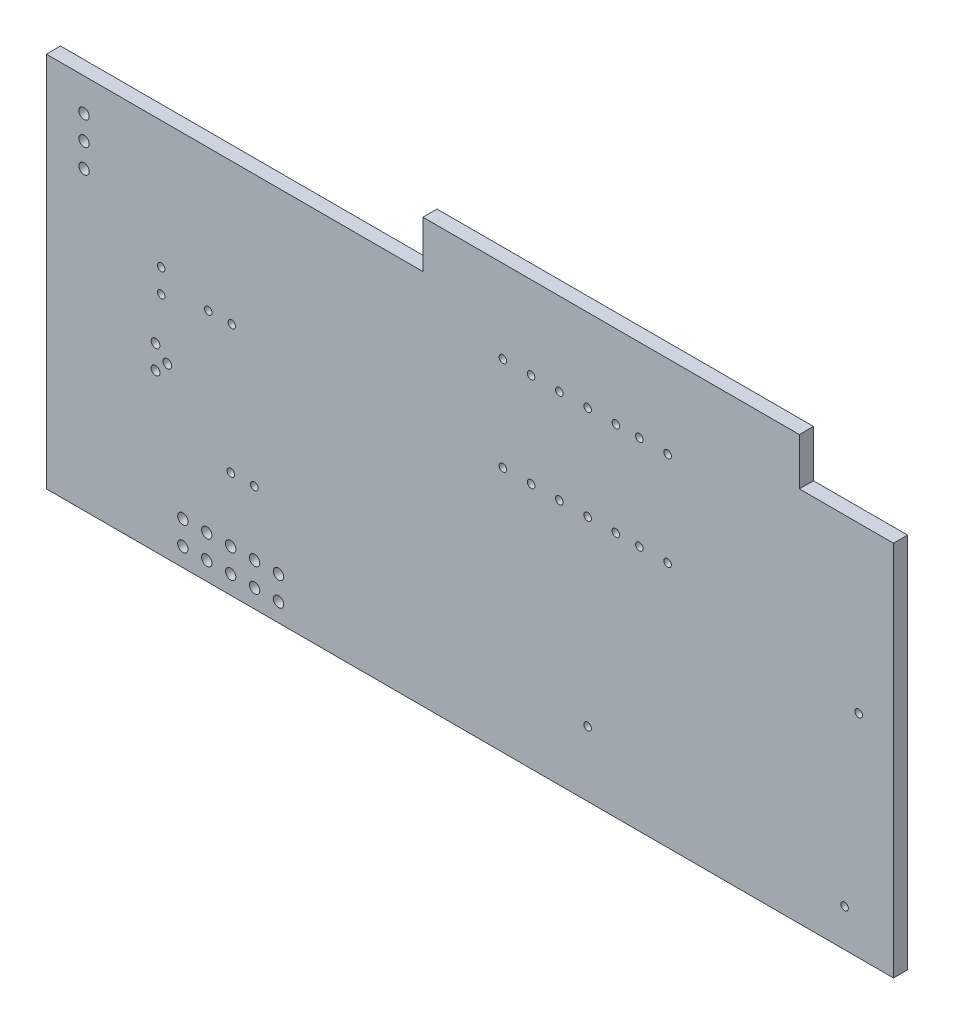
SolidWorks part; units mm, degrees
ref_plane "Спереди" through (0, 0, 0) normal (0, 0, 1) x (1, 0, 0)
ref_plane "Сверху" through (0, 0, 0) normal (0, 1, 0) x (1, 0, 0)
ref_plane "Справа" through (0, 0, 0) normal (1, 0, 0) x (0, 0, -1)
sketch "Эскиз1" plane through (0, 0, 0) normal (0, 0, 1) x (1, 0, 0)
  line L0 (0, 20) -> (0, 25)
  line L1 (-40, -20) -> (50, -20)
  line L2 (-40, -20) -> (-40, 20)
  line L3 (-40, 20) -> (0, 20)
  line L4 (50, -20) -> (50, 20)
  line L5 (0, 25) -> (40, 25)
  line L6 (40, 25) -> (40, 20)
  line L7 (40, 20) -> (50, 20)
  dimension "D1" = 90
  dimension "D2" = 40
  dimension "D3" = 40
  dimension "D4" = 40
  dimension "D5" = 5
  dimension "D6" = 20
extrude "Вытянуть1" add sketch "Эскиз1" along normal blind 1.5
sketch "Эскиз2" plane through (0, 0, 1.5) normal (0, 0, 1) x (1, 0, 0)
  line L0 (-40, 20) -> (-40, -20) construction
  line L1 (-40, -20) -> (50, -20) construction
  circle A0 centre (-36, 16.54) radius 0.55
  circle A1 centre (-36, 11.46) radius 0.55
  circle A2 centre (-36, 14) radius 0.55
  circle A3 centre (-25.5, -15.5) radius 0.55
  circle A4 centre (-25.5, -18.04) radius 0.55
  circle A5 centre (-22.96, -15.5) radius 0.55
  circle A6 centre (-22.96, -18.04) radius 0.55
  circle A7 centre (-20.42, -15.5) radius 0.55
  circle A8 centre (-20.42, -18.04) radius 0.55
  circle A9 centre (-17.88, -15.5) radius 0.55
  circle A10 centre (-17.88, -18.04) radius 0.55
  circle A11 centre (-15.34, -15.5) radius 0.55
  circle A12 centre (-15.34, -18.04) radius 0.55
  dimension "D1" = 5.08
  dimension "D3" = 36.54
  dimension "D4" = 1.1
  dimension "D5" = 2.54
  dimension "D8" = 1.1
  dimension "D9" = 2.54
  dimension "D2" = 4
  dimension "D6" = 4.5
  dimension "D7" = 14.5
  dimension "D10" = 14.5
extrude "Вырез-Вытянуть1" cut sketch "Эскиз2" against normal blind 1.5
sketch "Эскиз3" plane through (0, 0, 1.5) normal (0, 0, 1) x (1, 0, 0)
  line L0 (-40, -20) -> (50, -20) construction
  line L1 (-40, 20) -> (-40, -20) construction
  line L2 (8.5, 16.2) -> (8.5, 4.0182) construction
  line L3 (-40, -20) -> (50, -20) construction
  line L4 (8.5, 16.2) -> (28.1359, 16.2) construction
  line L5 (-40, 20) -> (-40, -20) construction
  line L6 (11.5, 16.2) -> (11.5, 4.0182) construction
  line L7 (14.5, 16.2) -> (14.5, 4.0182) construction
  line L8 (17.5, 16.2) -> (17.5, 4.0182) construction
  line L9 (20.5, 16.2) -> (20.5, 4.0182) construction
  line L10 (23.5, 16.2) -> (23.5, 4.0182) construction
  line L11 (26.5, 16.2) -> (26.5, 4.0182) construction
  line L12 (-20.4027, -8.7) -> (-16.725, -8.7) construction
  line L14 (-22.8, 5) -> (-16.1369, 5) construction
  line L15 (50, -20) -> (50, 20) construction
  line L20 (28.9777, 16.2) -> (21.3084, 16.2) construction
  line L30 (-31.875, 0.5) -> (-34.4855, 0.5) construction
  line L34 (-20.4027, -8.7) -> (-20.4027, -7.5412) construction
  line L35 (-20.4027, -7.5412) -> (-13.1239, -7.5412) construction
  line L36 (-22.8, 5) -> (-22.8, -7.5) construction
  line L37 (-27.8, 4) -> (-27.8, 6.5) construction
  circle A0 centre (-17.9027, -8.7) radius 0.4
  circle A1 centre (-20.3, 5) radius 0.4
  circle A12 centre (8.5, 16.2) radius 0.4
  circle A13 centre (8.5, 6.2) radius 0.4
  circle A16 centre (11.5, 16.2) radius 0.4
  circle A17 centre (11.5, 6.2) radius 0.4
  circle A18 centre (14.5, 16.2) radius 0.4
  circle A19 centre (14.5, 6.2) radius 0.4
  circle A20 centre (17.5, 16.2) radius 0.4
  circle A21 centre (17.5, 6.2) radius 0.4
  circle A22 centre (20.5, 16.2) radius 0.4
  circle A23 centre (20.5, 6.2) radius 0.4
  circle A42 centre (23, 16.2) radius 0.4
  circle A51 centre (23, 6.2) radius 0.4
  circle A52 centre (26, 16.2) radius 0.4
  circle A53 centre (26, 6.2) radius 0.4
  circle A71 centre (-20.4027, -8.7) radius 0.4
  circle A73 centre (-22.8, 5) radius 0.4
  circle A74 centre (-27.8, 6.5) radius 0.4
  circle A75 centre (-27.8, 4) radius 0.4
  dimension "D2" = 3
  dimension "D3" = 0.8
  dimension "D15" = 36.2
  dimension "D16" = 24
  dimension "D40" = 10
  dimension "D41" = 10
  dimension "D65" = 2.5
  dimension "D5" = 2.5
  dimension "D7" = 24
  dimension "D8" = 12.2
  dimension "D9" = 2.5
  dimension "D10" = 3
  dimension "D11" = 3
  dimension "D12" = 3
  dimension "D13" = 3
  dimension "D14" = 3
  dimension "D47" = 20.5
  dimension "D66" = 17.2
extrude "Вырез-Вытянуть2" cut sketch "Эскиз3" against normal blind 10
sketch "Эскиз6" plane through (0, 0, 1.5) normal (0, 0, 1) x (1, 0, 0)
  line L0 (-28.4, 1.4874) -> (-28.4, -3.7541) construction
  line L1 (-25.3934, -2.05) -> (-18.4226, -2.05) construction
  line L2 (-40, 20) -> (-40, -20) construction
  line L3 (-40, -20) -> (50, -20) construction
  line L4 (-40, -20) -> (50, -20) construction
  line L5 (50, -20) -> (50, 20) construction
  circle A0 centre (-28.4, -3.3) radius 0.465
  circle A1 centre (-28.4, -0.8) radius 0.465
  circle A2 centre (-27.15, -2.05) radius 0.465
  circle A4 centre (46.3, 2.5) radius 0.4
  circle A5 centre (17.5, -13.1) radius 0.4
  circle A7 centre (44.8, -16) radius 0.4
  dimension "D3" = 2.5
  dimension "D10" = 6.9
  dimension "D9" = 3.7
  dimension "D12" = 0.9301
  dimension "D2" = 16.7
  dimension "D4" = 2.5
  dimension "D1" = 11.6
  dimension "D8" = 22.5
  dimension "D11" = 32.5
  dimension "D14" = 4
  dimension "D15" = 5.2
extrude "Вырез-Вытянуть4" cut sketch "Эскиз6" against normal blind 10
